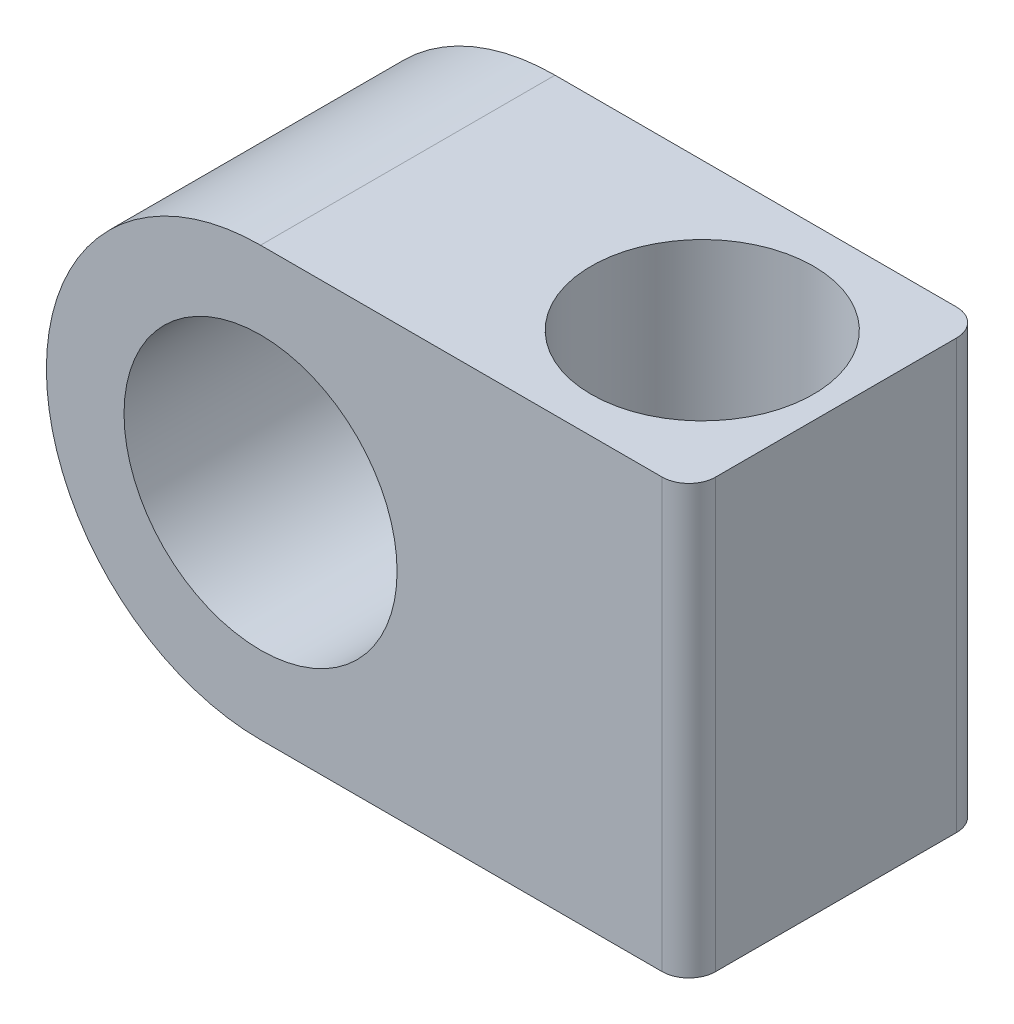
SolidWorks part; units mm, degrees
ref_plane "Alzado" through (0, 0, 0) normal (0, 0, 1) x (1, 0, 0)
ref_plane "Planta" through (0, 0, 0) normal (0, 1, 0) x (1, 0, 0)
ref_plane "Vista lateral" through (0, 0, 0) normal (1, 0, 0) x (0, 0, -1)
sketch "Croquis1" plane through (0, 0, 0) normal (0, 0, 1) x (1, 0, 0)
  circle A0 centre (0, 0) radius 8
extrude "Saliente-Extruir1" add sketch "Croquis1" along normal blind 11
sketch "Croquis2" plane through (0, 0, 0) normal (1, 0, 0) x (0, 0, -1)
  line L1 (-11, 8) -> (0, 8)
  line L2 (-11, 8) -> (-11, -8)
  line L3 (-11, -8) -> (0, -8)
  line L4 (0, 8) -> (0, -8)
extrude "Saliente-Extruir2" add sketch "Croquis2" along normal blind 16
sketch "Croquis3" plane through (0, 0, 11) normal (0, 0, 1) x (1, 0, 0)
  circle A0 centre (0, 0) radius 5.1
extrude "Cortar-Extruir1" cut sketch "Croquis3" against normal blind 20
sketch "Croquis4" plane through (0, 0, 0) normal (0, 1, 0) x (1, 0, 0)
  line L0 (16, -5.5) -> (-8, -5.5) construction
  line L1 (16, 0) -> (16, -11) construction
  line L2 (-8, 0) -> (-8, -11) construction
  circle A0 centre (11, -5.5) radius 4.15
  dimension "D1" = 5
extrude "Cortar-Extruir2" cut sketch "Croquis4" against normal through all both and the other way through all
fillet "Redondeo2" radius 1 1 edges at (16, 0, 0)
fillet "Redondeo3" radius 1 1 edges at (16, 0, 11)
